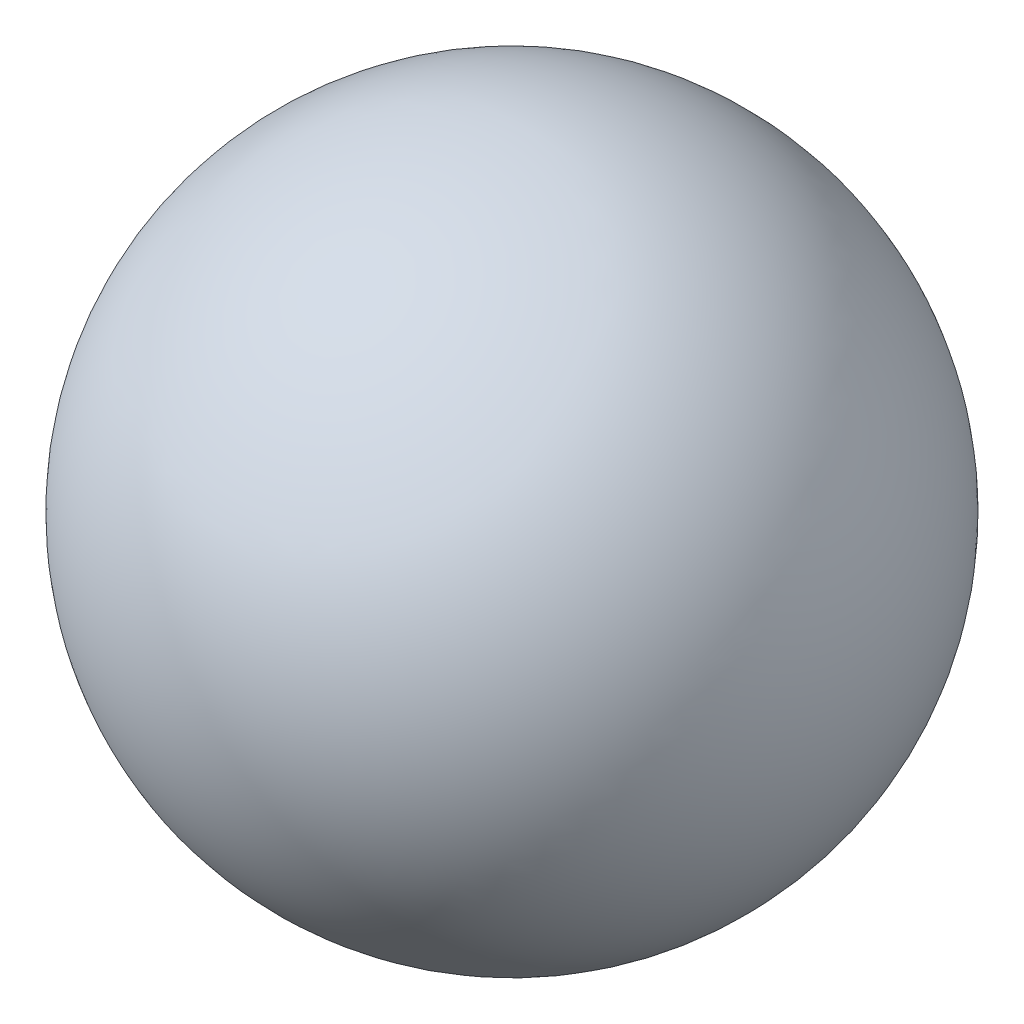
SolidWorks part; units mm, degrees
ref_plane "Front" through (0, 0, 0) normal (0, 0, 1) x (1, 0, 0)
ref_plane "Top" through (0, 0, 0) normal (0, 1, 0) x (1, 0, 0)
ref_plane "Right" through (0, 0, 0) normal (1, 0, 0) x (0, 0, -1)
sketch "Sketch2" plane through (0, 0, 0) normal (0, 1, 0) x (1, 0, 0)
  line L0 (0, 0) -> (0, 10) construction
  line L1 (0, 9.5) -> (3.3833, 9.5) construction
  line L2 (2.1794, 9.5) -> (0, 9.5)
  line L3 (0, 9.5) -> (0, 0)
  arc A0 (0, 10) -> (0, 0) centre (0, 5) cw construction
  arc A1 (2.1794, 9.5) -> (0, 0) centre (0, 5) cw
  dimension "D1" = 10
  dimension "D2" = 0.5
revolve "Revolve1" add sketch "Sketch2" angle 360 about L3
hole_wizard "M4x0.7 Tapped Hole1" positions "Sketch3" profile "Sketch5" tap size "M4x0.7" standard "ANSI Metric"
sketch "Sketch3" plane through (0, 0, -9.5) normal (0, 0, -1) x (-1, 0, 0)
  point P3 (0, 0)
sketch "Sketch5" plane through (0, 0, -9.5) normal (1, 0, 0) x (0, 1, 0)
  line L0 (0, 0) -> (0, 5.9914)
  line L1 (0, 5.9914) -> (1.65, 5)
  line L2 (1.65, 5) -> (1.65, 0)
  line L5 (1.65, 0) -> (0, 0)
  line L10 (0, 5.9914) -> (-1.65, 5) construction
  line L11 (0, -6.35) -> (0, 107.95) construction
  dimension "Tap Drill Dia." = 3.3
  dimension "Tap Drill Depth" = 5
  dimension "Drill Angle" = 118
cosmetic thread "Hole Thread1"
